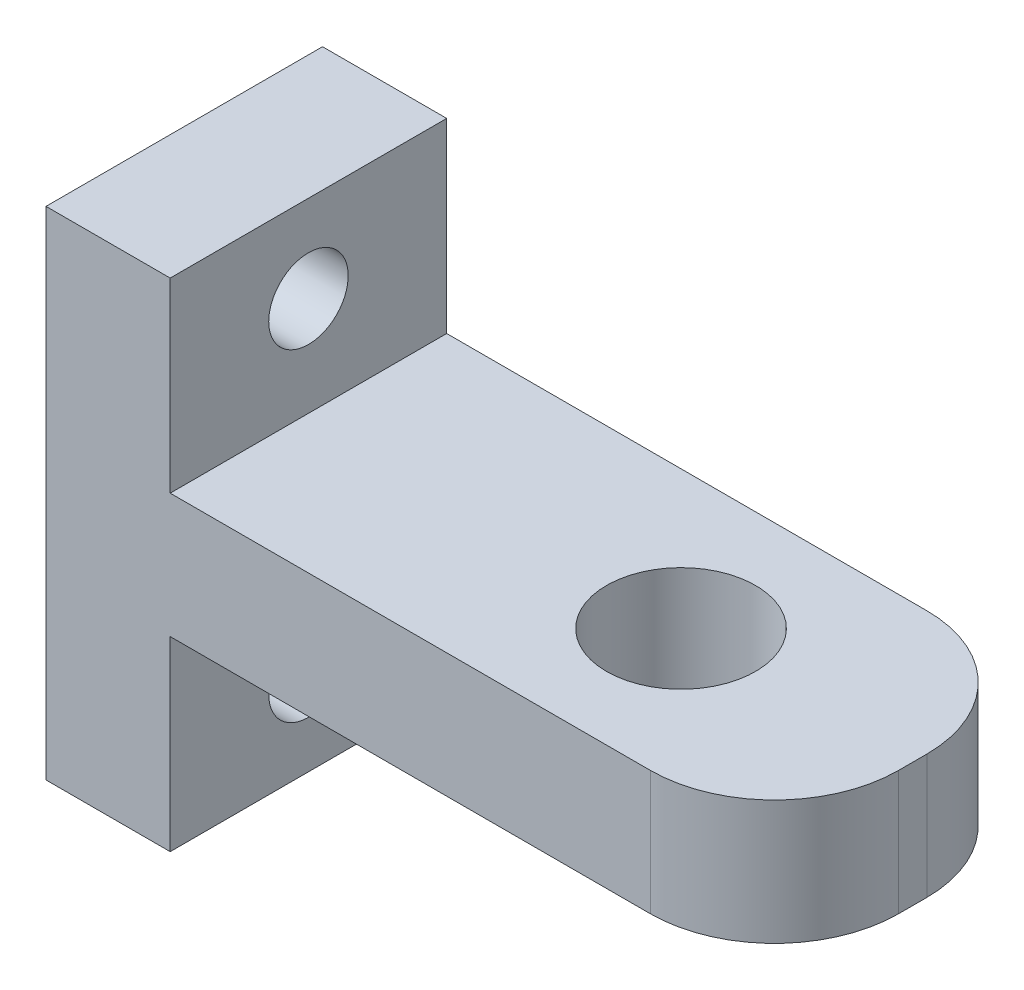
SolidWorks part; units mm, degrees
ref_plane "Front Plane" through (0, 0, 0) normal (0, 0, 1) x (1, 0, 0)
ref_plane "Top Plane" through (0, 0, 0) normal (0, 1, 0) x (1, 0, 0)
ref_plane "Right Plane" through (0, 0, 0) normal (1, 0, 0) x (0, 0, -1)
sketch "Sketch1" plane through (0, 0, 0) normal (0, 1, 0) x (1, 0, 0)
  line L1 (-15, 10) -> (15, 10)
  line L2 (-15, 10) -> (-15, -10)
  line L3 (-15, -10) -> (15, -10)
  line L4 (15, 10) -> (15, -10)
  line L5 (-15, 10) -> (15, -10) construction
  line L6 (-15, -10) -> (15, 10) construction
  point P0 (0, 0)
extrude "Boss-Extrude1" add sketch "Sketch1" along normal blind 5
sketch "Sketch2" plane through (0, 5, 0) normal (0, 1, 0) x (1, 0, 0)
  line L0 (-15, 10) -> (15, -10) construction
  line L1 (15, -10) -> (15, 10) construction
  line L2 (15, 10) -> (-15, -10) construction
  circle A0 centre (0, 0) radius 3
extrude "Cut-Extrude1" cut sketch "Sketch2" against normal blind 10
sketch "Sketch3" plane through (0, 5, 0) normal (0, 1, 0) x (1, 0, 0)
  line L0 (0, 3) -> (0, 5.5664) construction
  line L1 (0, 0) -> (2.0476, 0) construction
  line L2 (0, -3) -> (0, -5.5664) construction
  line L3 (-15, 10) -> (-15, -10) construction
  line L4 (-15, 5.5664) -> (9.3279, 5.5664)
  line L5 (-15, 5.5664) -> (-15, -5.5664)
  line L6 (-15, -5.5664) -> (9.3279, -5.5664)
  line L7 (9.3279, 5.5664) -> (9.3279, -5.5664)
  circle A0 centre (0, 0) radius 3 construction
extrude "Cut-Extrude2" cut sketch "Sketch3" against normal blind 10 flip side to cut
sketch "Sketch4" plane through (-15, 0, 0) normal (-1, 0, 0) x (0, 0, 1)
  line L0 (-5.5664, 5) -> (5.5664, 0) construction
  line L1 (5.5664, 0) -> (5.5664, 5) construction
  line L2 (5.5664, 0) -> (5.5664, 5) construction
  line L3 (5.5664, 5) -> (-5.5664, 0) construction
  line L5 (-5.5664, -7.5) -> (5.5664, -7.5)
  line L6 (-5.5664, -7.5) -> (-5.5664, 12.5)
  line L7 (-5.5664, 12.5) -> (5.5664, 12.5)
  line L8 (5.5664, -7.5) -> (5.5664, 12.5)
  line L9 (-5.5664, -7.5) -> (5.5664, 12.5) construction
  line L10 (-5.5664, 12.5) -> (5.5664, -7.5) construction
  point P4 (0, 2.5)
extrude "Boss-Extrude2" add sketch "Sketch4" along normal blind 5
sketch "Sketch5" plane through (-20, 0, 0) normal (-1, 0, 0) x (0, 0, 1)
  line L0 (-5.5664, 12.5) -> (5.5664, -7.5) construction
  line L1 (0, 2.5) -> (0, 9) construction
  line L2 (0, 2.5) -> (3.206, 2.5) construction
  circle A0 centre (0, 9) radius 1.6
  circle A1 centre (0, -4) radius 1.6
extrude "Cut-Extrude3" cut sketch "Sketch5" against normal blind 5
fillet "Fillet2" radius 5 2 edges at (9.3279, 2.5, -5.5664) (9.3279, 2.5, 5.5664)
